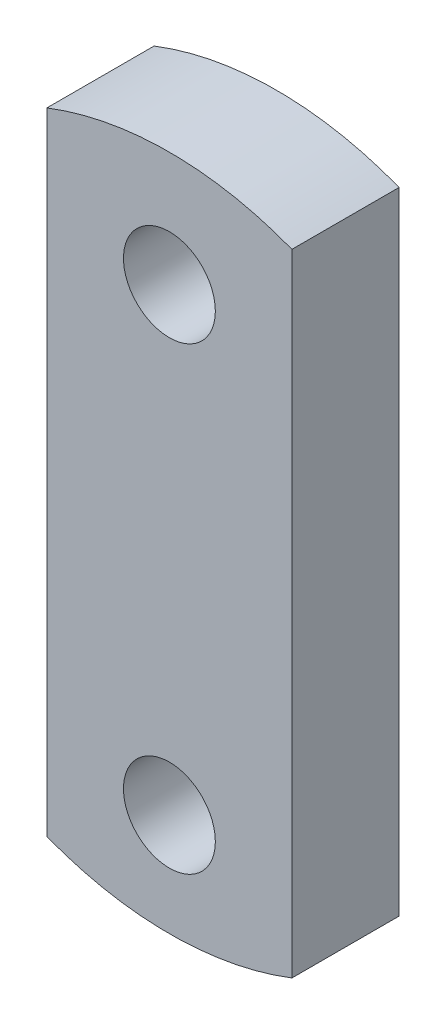
SolidWorks part; units mm, degrees
ref_plane "Front Plane" through (0, 0, 0) normal (0, 0, 1) x (1, 0, 0)
ref_plane "Top Plane" through (0, 0, 0) normal (0, 1, 0) x (1, 0, 0)
ref_plane "Right Plane" through (0, 0, 0) normal (1, 0, 0) x (0, 0, -1)
sketch "Sketch1" plane through (0, 0, 0) normal (0, 0, 1) x (1, 0, 0)
  line L3 (-40, -101.0714) -> (-40, 104.9935)
  line L5 (40, 104.9935) -> (40, -101.0714)
  arc A5 (-40, -101.0714) -> (40, -101.0714) centre (0, 1.961) ccw
  arc A6 (40, 104.9935) -> (-40, 104.9935) centre (0, 1.961) ccw
extrude "Boss-Extrude1" add sketch "Sketch1" along normal blind 35
sketch "Sketch2" plane through (0, 0, 0) normal (0, 0, 1) x (1, 0, 0)
  circle A0 centre (0, 74.9935) radius 15
extrude "Cut-Extrude1" cut sketch "Sketch2" against normal through all and the other way through all
sketch "Sketch3" plane through (0, 0, 0) normal (0, 0, 1) x (1, 0, 0)
  circle A0 centre (0, -75.0065) radius 15
extrude "Cut-Extrude2" cut sketch "Sketch3" against normal through all and the other way through all
